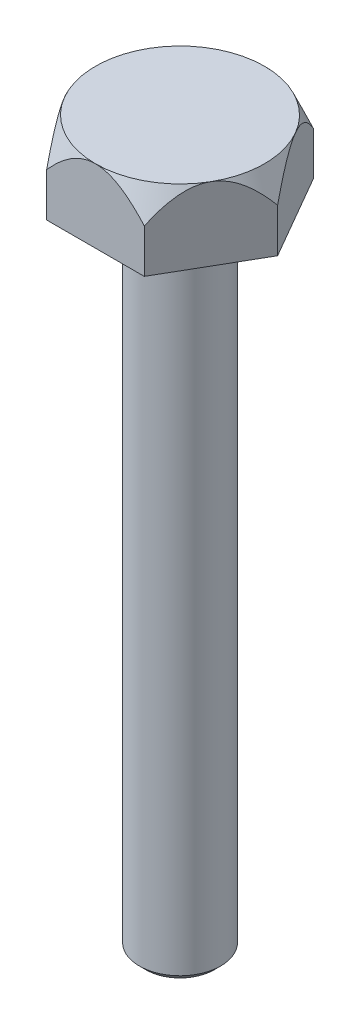
SolidWorks part; units mm, degrees
ref_plane "Front Plane" through (0, 0, 0) normal (0, 0, 1) x (1, 0, 0)
ref_plane "Top Plane" through (0, 0, 0) normal (0, 1, 0) x (1, 0, 0)
ref_plane "Right Plane" through (0, 0, 0) normal (1, 0, 0) x (0, 0, -1)
sketch "Sketch1" plane through (0, 0, 0) normal (0, 1, 0) x (1, 0, 0)
  line L1 (30.0222, -52) -> (60.0444, 0)
  line L2 (60.0444, 0) -> (30.0222, 52)
  line L3 (30.0222, 52) -> (-30.0222, 52)
  line L4 (-30.0222, 52) -> (-60.0444, 0)
  line L5 (-60.0444, 0) -> (-30.0222, -52)
  line L6 (-30.0222, -52) -> (30.0222, -52)
  circle A0 centre (0, 0) radius 52 construction
  dimension "D1" = 104
extrude "Boss-Extrude1" add sketch "Sketch1" along normal blind 45
sketch "Sketch2" plane through (0, 45, 0) normal (0, 1, 0) x (1, 0, 0)
  circle A0 centre (0, 0) radius 52
extrude "Cut-Extrude2" cut sketch "Sketch2" against normal through all draft 24 flip side to cut
sketch "Sketch3" plane through (0, 0, 0) normal (0, -1, 0) x (1, 0, 0)
  circle A0 centre (0, 0) radius 25
  dimension "D1" = 50
extrude "Boss-Extrude2" add sketch "Sketch3" along normal blind 400
chamfer "Chamfer1" distance 4 angle 45 1 edges at (0, -400, -25)
